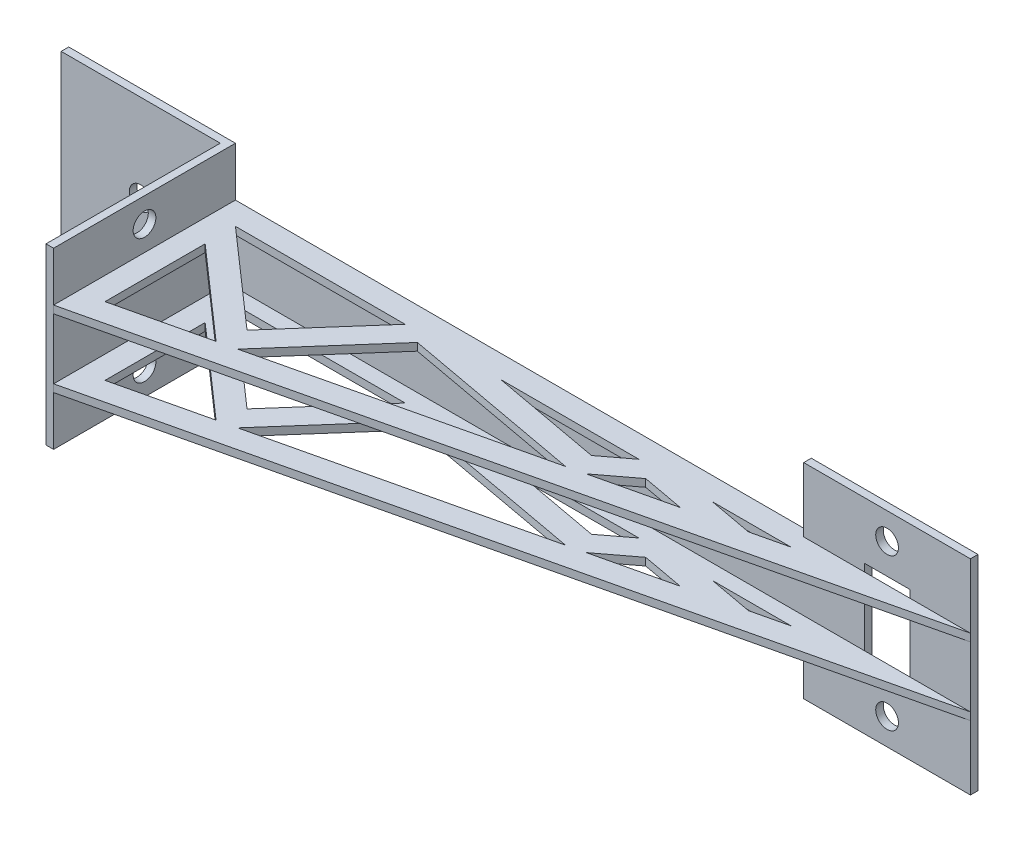
SolidWorks part; units mm, degrees
ref_plane "Front Plane" through (0, 0, 0) normal (0, 0, 1) x (1, 0, 0)
ref_plane "Top Plane" through (0, 0, 0) normal (0, 1, 0) x (1, 0, 0)
ref_plane "Right Plane" through (0, 0, 0) normal (1, 0, 0) x (0, 0, -1)
sketch "Sketch1" plane through (0, 0, 0) normal (0, 0, 1) x (1, 0, 0)
  line L1 (-60, 12.5) -> (60, 12.5)
  line L2 (-60, 12.5) -> (-60, -12.5)
  line L3 (-60, -12.5) -> (60, -12.5)
  line L4 (60, 12.5) -> (60, -12.5)
  line L5 (-60, 12.5) -> (60, -12.5) construction
  line L6 (-60, -12.5) -> (60, 12.5) construction
  point P0 (0, 0)
  dimension "D1" = 120
  dimension "D2" = 25
extrude "Boss-Extrude4" add sketch "Sketch1" along normal blind 1
sketch "Sketch6" plane through (0, 0, 0) normal (0, 0, -1) x (-1, 0, 0)
  line L0 (-60, 12.5) -> (60, 12.5) construction
  line L1 (38, 12.5) -> (-38, 12.5)
  line L2 (38, 12.5) -> (38, 5)
  line L3 (38, 5) -> (-38, 5)
  line L4 (-38, 12.5) -> (-38, 5)
  line L5 (60, -12.5) -> (-60, -12.5) construction
  line L6 (38, -12.5) -> (-38, -12.5)
  line L7 (38, -12.5) -> (38, -5)
  line L8 (38, -5) -> (-38, -5)
  line L9 (-38, -12.5) -> (-38, -5)
  line L10 (38, -12.5) -> (60, -12.5) construction
  line L11 (-38, -12.5) -> (-60, -12.5) construction
  line L12 (60, 12.5) -> (60, -12.5) construction
  dimension "D1" = 10
  dimension "D2" = 22
extrude "Cut-Extrude1" cut sketch "Sketch6" against normal through all
sketch "Sketch7" plane through (0, 0, 1) normal (0, 0, 1) x (1, 0, 0)
  line L0 (-60, -12.5) -> (-38, -12.5) construction
  line L1 (-38, 12.5) -> (-39, 12.5)
  line L2 (-38, 12.5) -> (-38, -12.5)
  line L3 (-38, -12.5) -> (-39, -12.5)
  line L4 (-39, 12.5) -> (-39, -12.5)
  dimension "D1" = 1
extrude "Boss-Extrude5" add sketch "Sketch7" along normal blind 23
sketch "Sketch11" plane through (0, 0, 0) normal (0, 0, -1) x (-1, 0, 0)
  line L0 (-60, 0) -> (-32.9424, 0) construction
  line L1 (-60, -12.5) -> (-60, 12.5) construction
  line L3 (-49, 12.5) -> (-49, -12.5) construction
  line L4 (-60, 12.5) -> (-38, 12.5) construction
  line L5 (-49, 10) -> (-49, -10) construction
  line L6 (-46, 6) -> (-52, 6)
  line L7 (-46, 6) -> (-46, -6)
  line L8 (-46, -6) -> (-52, -6)
  line L9 (-52, 6) -> (-52, -6)
  line L10 (-46, 6) -> (-52, -6) construction
  line L11 (-46, -6) -> (-52, 6) construction
  line L12 (-38, -12.5) -> (-60, -12.5) construction
  circle A0 centre (-49, 10) radius 1.5
  circle A1 centre (-49, -10) radius 1.5
  point P5 (-49, 0)
  point P8 (0, 0)
  point P15 (-49, 0)
  dimension "D3" = 3
  dimension "D4" = 3
  dimension "D5" = 17
  dimension "D1" = 12
  dimension "D2" = 6
extrude "Cut-Extrude3" cut sketch "Sketch11" against normal through all
sketch "Sketch10" plane through (0, 5, 0) normal (0, 1, 0) x (1, 0, 0)
  line L0 (-38, -1) -> (-38, -24)
  line L1 (-38, -24) -> (60, -1)
  line L2 (60, -1) -> (-38, -1)
  line L3 (-38, -24) -> (-39, -24) construction
  line L4 (60, -1) -> (60, 0) construction
  line L5 (47.5, -1) -> (50.5, -1) construction
  point P0 (0, 0)
sketch "Sketch14" plane through (0, 12.5, 0) normal (0, 1, 0) x (1, 0, 0)
  line L6 (-60, -1) -> (-39, -1)
  line L7 (-39, -1) -> (-39, -24)
  line L8 (-39, -24) -> (-38, -24)
  line L9 (-38, -24) -> (-38, 0)
  line L10 (-38, 0) -> (-60, 0)
  line L11 (-60, 0) -> (-60, -1)
  line L12 (-60, -1) -> (-39, -1)
  line L13 (-39, -1) -> (-39, -24)
  line L14 (-39, -24) -> (-38, -24)
  line L15 (-38, -24) -> (-38, 0)
  line L16 (-38, 0) -> (-60, 0)
  line L17 (-60, 0) -> (-60, -1)
  dimension "D1" = 0
extrude "Cut-Extrude4" cut sketch "Sketch14" against normal blind 1
sketch "Sketch15" plane through (0, -12.5, 0) normal (0, -1, 0) x (1, 0, 0)
  line L6 (-60, 0) -> (-38, 0)
  line L7 (-38, 0) -> (-38, 24)
  line L8 (-38, 24) -> (-39, 24)
  line L9 (-39, 24) -> (-39, 1)
  line L10 (-39, 1) -> (-60, 1)
  line L11 (-60, 1) -> (-60, 0)
  line L12 (-60, 0) -> (-38, 0)
  line L13 (-38, 0) -> (-38, 24)
  line L14 (-38, 24) -> (-39, 24)
  line L15 (-39, 24) -> (-39, 1)
  line L16 (-39, 1) -> (-60, 1)
  line L17 (-60, 1) -> (-60, 0)
  dimension "D1" = 0
extrude "Cut-Extrude5" cut sketch "Sketch15" against normal blind 1
extrude "Boss-Extrude6" add sketch "Sketch10" against normal blind 1
ref_plane "Plane1" through (0, 0, 0) normal (0, -1, 0) x (-1, 0, 0)
mirror "Mirror1" about plane through (0, 0, 0) normal (0, -1, 0) of "Boss-Extrude6"
sketch "Sketch13" plane through (0, -12.5, 0) normal (0, -1, 0) x (-1, 0, 0)
  line L1 (-60, -1) -> (-38, -1)
  line L2 (-60, -1) -> (-60, 0)
  line L3 (-60, 0) -> (-38, 0)
  line L4 (-38, -1) -> (-38, 0)
extrude "Boss-Extrude7" add sketch "Sketch13" along normal blind 1
mirror "Mirror2" about plane through (0, 0, 0) normal (0, -1, 0) of "Boss-Extrude7"
sketch "Sketch16" plane through (-38, 0, 0) normal (1, 0, 0) x (0, 0, -1)
  line L0 (-12, 11.5) -> (-12, -11.5) construction
  line L1 (-24, 11.5) -> (0, 11.5) construction
  line L2 (0, -11.5) -> (-24, -11.5) construction
  line L3 (0, 8.25) -> (-24, 8.25) construction
  line L4 (0, 5) -> (0, 11.5) construction
  line L5 (-24, 5) -> (-24, 11.5) construction
  line L6 (-24, 8.25) -> (-24, -8.25) construction
  line L7 (-24, -11.5) -> (-24, -5) construction
  line L8 (-24, -8.25) -> (0, -8.25) construction
  line L9 (0, -11.5) -> (0, -5) construction
  circle A0 centre (-12, -8.25) radius 1.5
  circle A1 centre (-12, 8.25) radius 1.5
  point P16 (0, 0)
  point P23 (0, 0)
  dimension "D1" = 3
  dimension "D2" = 3
extrude "Cut-Extrude6" cut sketch "Sketch16" against normal up to surface (1 mm away) up to face at (-39, 0, 12.5)
sketch "Sketch17" plane through (0, 0, 1) normal (0, 0, 1) x (1, 0, 0)
  line L0 (-60, -11.5) -> (-39, 11.5) construction
  circle A0 centre (-49.5, 0) radius 1.5
  dimension "D1" = 3
extrude "Cut-Extrude7" cut sketch "Sketch17" against normal up to surface (1 mm away) up to face at (47.5, 10, 0)
sketch "Sketch18" plane through (0, 5, 0) normal (0, 1, 0) x (1, 0, 0)
  line L0 (-35, -6.9941) -> (-35, -20.2144)
  line L1 (-35, -20.2144) -> (-23.1285, -17.4282)
  line L2 (38.3483, -3) -> (27.9534, -3)
  line L3 (-38, -24) -> (60, -1) construction
  line L4 (38, 0) -> (-38, 0) construction
  line L5 (-38, -24) -> (-38, 0) construction
  line L6 (-35, -3) -> (-22.3664, -14.104)
  line L7 (-20.8174, -16.8858) -> (-9.7239, -4.2642)
  line L8 (-9.7239, -4.2642) -> (14.2221, -8.6623)
  line L9 (14.6903, -5.6981) -> (18.2535, -3)
  line L10 (20.9047, -4.7556) -> (26.494, -5.7821)
  line L11 (-35, -6.9941) -> (-23.1285, -17.4282)
  line L12 (-22.3664, -14.104) -> (-12.6068, -3)
  line L13 (0, -3) -> (14.6903, -5.6981)
  line L14 (16.4293, -8.1443) -> (20.9047, -4.7556)
  line L15 (27.9534, -3) -> (33.7848, -4.071)
  line L16 (-20.8174, -16.8858) -> (14.2221, -8.6623)
  line L17 (-12.6068, -3) -> (-35, -3)
  line L18 (16.4293, -8.1443) -> (26.494, -5.7821)
  line L19 (18.2535, -3) -> (0, -3)
  line L20 (33.7848, -4.071) -> (38.3483, -3)
  point P24 (16.4719, -4.349)
  dimension "D1" = 3
  dimension "D2" = 3
  dimension "D3" = 3
  dimension "D4" = 3
  dimension "D5" = 3
  dimension "D6" = 3
  dimension "D7" = 3
  dimension "D8" = 3
extrude "Cut-Extrude8" cut sketch "Sketch18" against normal up to surface (10 mm away) up to face at (22.5714, -5, 4)
